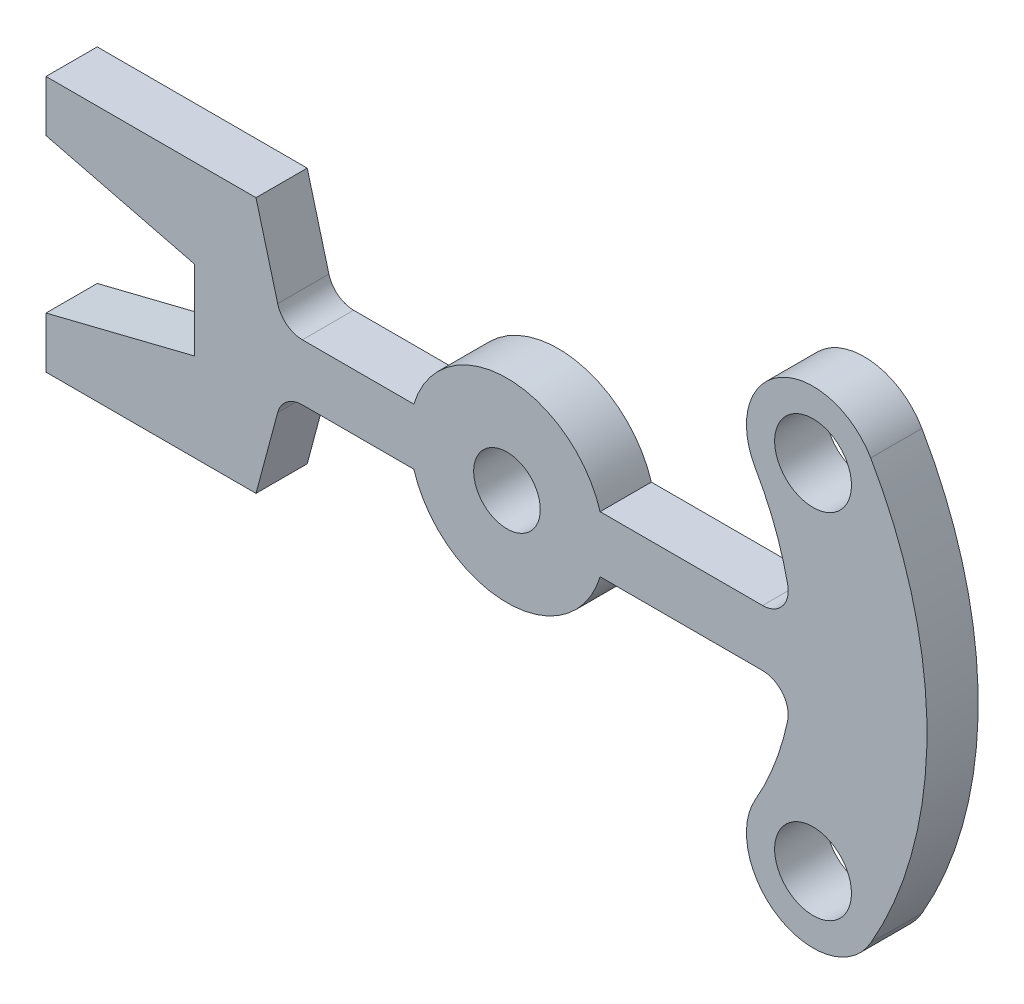
SolidWorks part; units mm, degrees
ref_plane "Front Plane" through (0, 0, 0) normal (0, 0, 1) x (1, 0, 0)
ref_plane "Top Plane" through (0, 0, 0) normal (0, 1, 0) x (1, 0, 0)
ref_plane "Right Plane" through (0, 0, 0) normal (1, 0, 0) x (0, 0, -1)
sketch "Sketch1" plane through (0, 0, 0) normal (0, 0, 1) x (1, 0, 0)
  line L1 (-90, 25) -> (-90, 15)
  line L2 (18.1865, -5.5) -> (49.9074, -5.5)
  line L3 (-18.1865, -5.5) -> (-39.9384, -5.5)
  line L4 (-90, 25) -> (-49, 25)
  line L5 (-90, -25) -> (-61, -25)
  line L6 (-49, 25) -> (-44.768, 9.2059)
  line L7 (-90, 15) -> (-61, 7.7695)
  line L8 (-90, 25) -> (-61, 25)
  line L9 (-61, 7.7695) -> (-61, -7.7695)
  line L10 (-90, -15) -> (-61, -7.7695)
  line L11 (0, 0) -> (9.5263, 5.5)
  line L13 (18.1865, 5.5) -> (49.9074, 5.5)
  line L14 (-18.1865, 5.5) -> (-39.9384, 5.5)
  line L15 (-49, -25) -> (-44.768, -9.2059)
  line L16 (-90, -25) -> (-49, -25)
  line L17 (-90, -25) -> (-90, -15)
  circle A0 centre (0, 0) radius 6.5
  arc A1 (18.1865, 5.5) -> (-18.1865, 5.5) centre (0, 0) ccw
  arc A3 (-44.768, 9.2059) -> (-39.9384, 5.5) centre (-39.9384, 10.5) ccw
  circle A7 centre (59.7558, 34.5) radius 7.5
  arc A8 (71.0141, 41) -> (48.4974, 28) centre (59.7558, 34.5) ccw
  arc A9 (71.0141, -41) -> (71.0141, 41) centre (0, 0) ccw
  arc A10 (49.9074, 5.5) -> (54.8003, 11.5294) centre (49.9074, 10.5) ccw
  arc A11 (54.8003, 11.5294) -> (48.4974, 28) centre (0, 0) ccw
  arc A12 (54.8003, -11.5294) -> (48.4974, -28) centre (0, 0) cw
  arc A13 (49.9074, -5.5) -> (54.8003, -11.5294) centre (49.9074, -10.5) cw
  arc A14 (71.0141, -41) -> (48.4974, -28) centre (59.7558, -34.5) cw
  circle A15 centre (59.7558, -34.5) radius 7.5
  arc A16 (-44.768, -9.2059) -> (-39.9384, -5.5) centre (-39.9384, -10.5) cw
  arc A17 (18.1865, -5.5) -> (-18.1865, -5.5) centre (0, 0) cw
  dimension "D1" = 13
  dimension "D3" = 104
  dimension "D2" = 5
  dimension "D4" = 15
  dimension "D5" = 19
  dimension "D6" = 13
  dimension "D7" = 82
  dimension "D8" = 9.5263
  dimension "D9" = 18.1865
  dimension "D10" = 90
  dimension "D11" = 7.7695
  dimension "D18" = 61
extrude "Boss-Extrude1" add sketch "Sketch1" along normal blind 10
